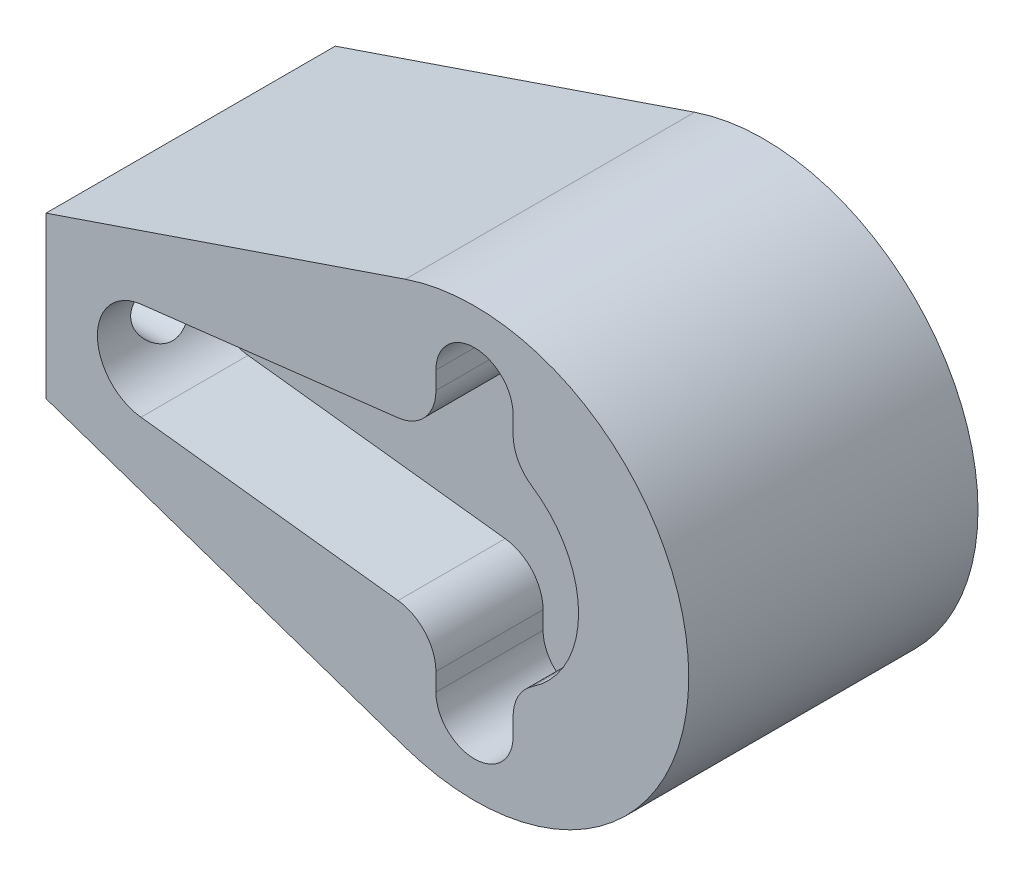
SolidWorks part; units mm, degrees
ref_plane "Спереди" through (0, 0, 0) normal (0, 0, 1) x (1, 0, 0)
ref_plane "Сверху" through (0, 0, 0) normal (0, 1, 0) x (1, 0, 0)
ref_plane "Справа" through (0, 0, 0) normal (1, 0, 0) x (0, 0, -1)
sketch "Эскиз1" plane through (0, 0, 0) normal (0, 0, 1) x (1, 0, 0)
  line L6 (1.8, 5.7088) -> (1.8, 6.512)
  line L7 (-1.8, 6.512) -> (-1.8, 5.679)
  line L8 (-3.5669, 3.6927) -> (-15.5681, 2.2843)
  line L9 (-15.5681, -2.2843) -> (-3.5669, -3.6927)
  line L10 (-1.8, -5.679) -> (-1.8, -6.512)
  line L11 (1.8, -6.512) -> (1.8, -5.7088)
  line L12 (-20, 3.75) -> (-20, -3.75)
  line L13 (-20, 3.75) -> (-3.2252, 9.4656)
  line L15 (-3.2252, -9.4656) -> (-20, -3.75)
  arc A5 (1.8, 6.512) -> (-1.8, 6.512) centre (0, 6.512) ccw
  arc A6 (-15.5681, 2.2843) -> (-15.5681, -2.2843) centre (-15.3, 0) ccw
  arc A7 (-1.8, -6.512) -> (1.8, -6.512) centre (0, -6.512) ccw
  arc A8 (-3.2252, -9.4656) -> (-3.2252, 9.4656) centre (0, 0) ccw
  arc A9 (2.6918, 4.0439) -> (2.6918, -4.0439) centre (0, 0) cw
  arc A10 (-1.8, -5.679) -> (-3.5669, -3.6927) centre (-3.8, -5.679) ccw
  arc A11 (-1.8, 5.679) -> (-3.5669, 3.6927) centre (-3.8, 5.679) cw
  arc A12 (2.6918, -4.0439) -> (1.8, -5.7088) centre (3.8, -5.7088) ccw
  arc A13 (2.6918, 4.0439) -> (1.8, 5.7088) centre (3.8, 5.7088) cw
  point P44 (-1.8, -3.9)
  point P47 (-1.8, 3.9)
  point P52 (1.8, 4.512)
  dimension "D3" = 2.3
  dimension "D4" = 1.8
  dimension "D5" = 7.8
  dimension "D9" = 20
  dimension "D12" = 2
  dimension "D13" = 2
  dimension "D1" = 3.6
  dimension "D2" = 15.3
  dimension "D6" = 2
  dimension "D7" = 1.8
  dimension "D8" = 2.612
  dimension "D10" = 7.5
  dimension "D11" = 20
extrude "Бобышка-Вытянуть1" add sketch "Эскиз1" along normal blind 5
sketch "Эскиз2" plane through (0, 0, 5) normal (0, 0, 1) x (1, 0, 0)
  line L3 (-3.2252, 9.4656) -> (-20, 3.75)
  line L4 (-20, 3.75) -> (-20, -3.75)
  line L5 (-20, -3.75) -> (-3.2252, -9.4656)
  line L6 (-3.2252, 9.4656) -> (-20, 3.75)
  line L7 (-20, 3.75) -> (-20, -3.75)
  line L8 (-20, -3.75) -> (-3.2252, -9.4656)
  arc A1 (-3.2252, -9.4656) -> (-3.2252, 9.4656) centre (0, 0) ccw
  arc A2 (-3.2252, -9.4656) -> (-3.2252, 9.4656) centre (0, 0) ccw
  dimension "D1" = 0
extrude "Бобышка-Вытянуть2" add sketch "Эскиз2" against normal blind 8.5 from surface at -5 starting at face at (-8.3063, 0, 0)
sketch "Эскиз3" plane through (0, 0, -8.5) normal (0, 0, -1) x (-1, 0, 0)
  circle A0 centre (0, 0) radius 2.75
  dimension "D1" = 5.5
extrude "Бобышка-Вытянуть3" add sketch "Эскиз3" along normal blind 3
sketch "Эскиз4" plane through (-20, 0, 0) normal (-1, 0, 0) x (0, 0, 1)
  line L0 (-1000, 0) -> (49000, 0) construction
  line L2 (-8.5, 2.75) -> (-8.5, -2.75) construction
  line L3 (5, 3.75) -> (5, -3.75) construction
  circle A0 centre (-5.5, 0) radius 1.45
  circle A1 centre (2, 0) radius 1.45
  dimension "D1" = 2.9
  dimension "D2" = 3
  dimension "D3" = 3
extrude "Вырез-Вытянуть1" cut sketch "Эскиз4" against normal blind 7
